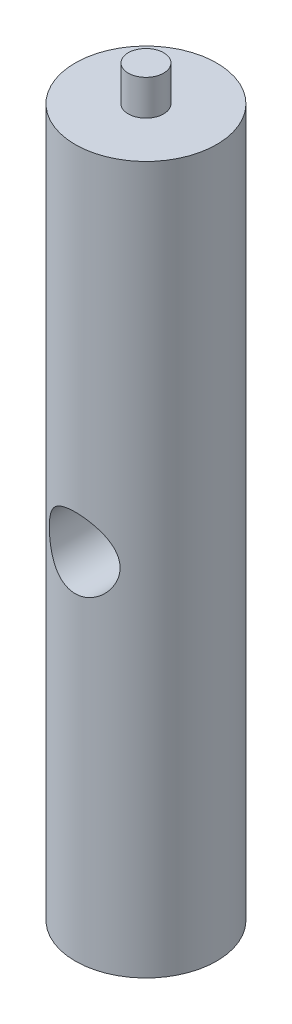
SolidWorks part; units mm, degrees
material "ABS"
ref_plane "Front Plane" through (0, 0, 0) normal (0, 0, 1) x (1, 0, 0)
ref_plane "Top Plane" through (0, 0, 0) normal (0, 1, 0) x (1, 0, 0)
ref_plane "Right Plane" through (0, 0, 0) normal (1, 0, 0) x (0, 0, -1)
sketch "Sketch1" plane through (0, 0, 0) normal (0, 1, 0) x (1, 0, 0)
  circle A0 centre (0, 0) radius 20
extrude "Boss-Extrude1" add sketch "Sketch1" along normal blind 200
sketch "Sketch2" plane through (0, 0, 0) normal (0, 0, 1) x (1, 0, 0)
  circle A0 centre (0, 100) radius 10
extrude "Cut-Extrude1" cut sketch "Sketch2" against normal blind 200 and the other way through all
sketch "Sketch5" plane through (0, 200, 0) normal (0, 1, 0) x (1, 0, 0)
  circle A0 centre (0, 0) radius 5
extrude "Boss-Extrude4" add sketch "Sketch5" along normal blind 10
